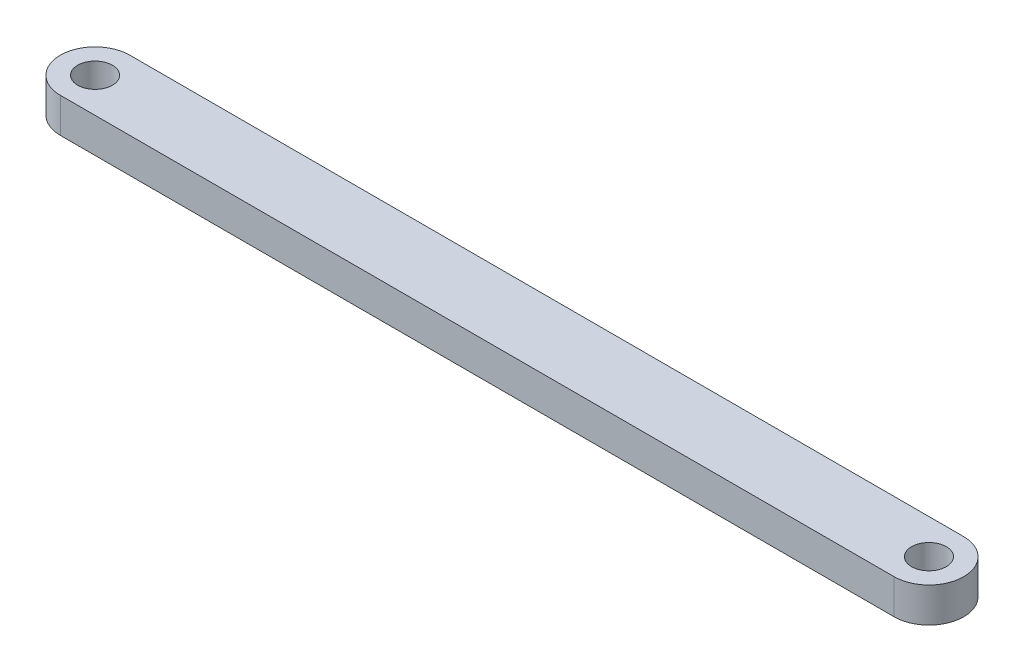
SolidWorks part; units mm, degrees
ref_plane "Front Plane" through (0, 0, 0) normal (0, 0, 1) x (1, 0, 0)
ref_plane "Top Plane" through (0, 0, 0) normal (0, 1, 0) x (1, 0, 0)
ref_plane "Right Plane" through (0, 0, 0) normal (1, 0, 0) x (0, 0, -1)
sketch "Sketch1" plane through (0, 0, 0) normal (0, 1, 0) x (1, 0, 0)
  line L0 (0, 127) -> (3048, 127)
  line L1 (0, -127) -> (3048, -127)
  arc A0 (0, 127) -> (0, -127) centre (0, 0) ccw
  arc A1 (3048, -127) -> (3048, 127) centre (3048, 0) ccw
  circle A2 centre (0, 0) radius 63.5
  circle A3 centre (3048, 0) radius 63.5
  dimension "D2" = 254
  dimension "D3" = 127
  dimension "D1" = 3048
extrude "Boss-Extrude1" add sketch "Sketch1" along normal blind 127
